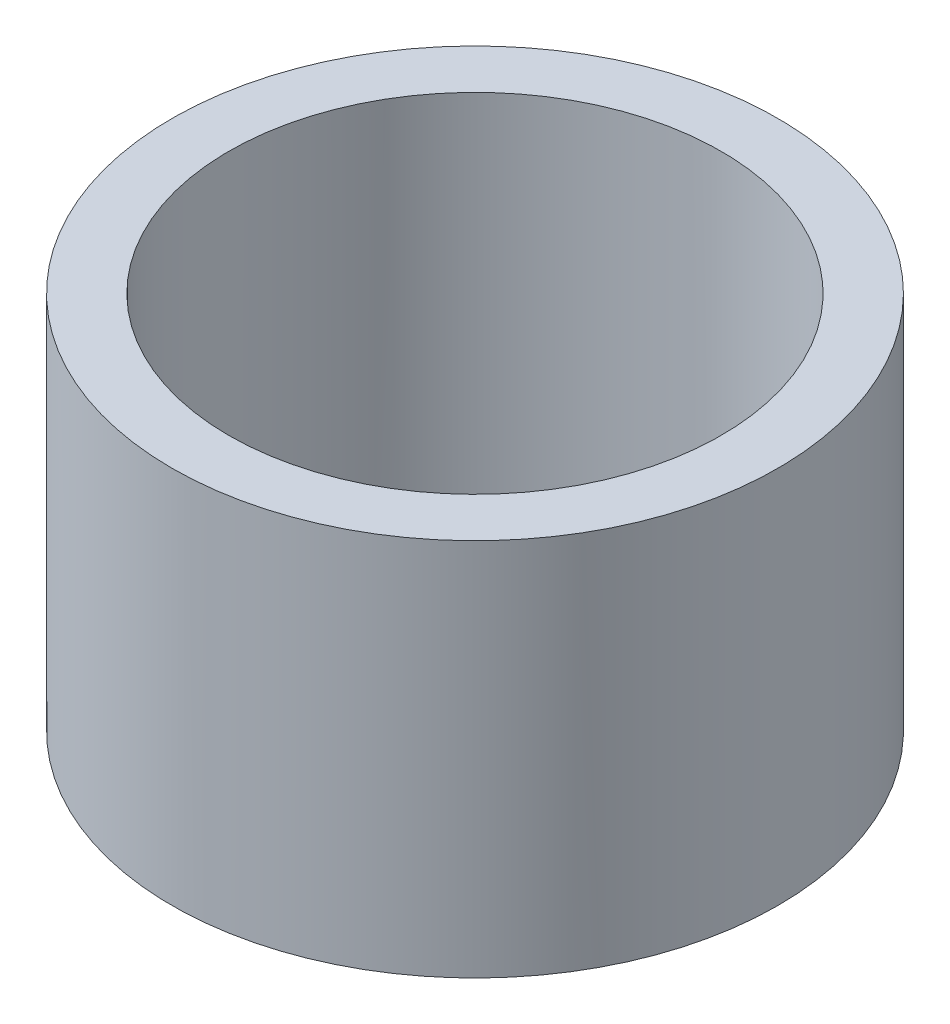
SolidWorks part; units mm, degrees
ref_plane "Front Plane" through (0, 0, 0) normal (0, 0, 1) x (1, 0, 0)
ref_plane "Top Plane" through (0, 0, 0) normal (0, 1, 0) x (1, 0, 0)
ref_plane "Right Plane" through (0, 0, 0) normal (1, 0, 0) x (0, 0, -1)
sketch "Sketch1" plane through (0, 0, 0) normal (0, 1, 0) x (1, 0, 0)
  circle A0 centre (0, 0) radius 20.32
extrude "Boss-Extrude1" add sketch "Sketch1" along normal blind 25.4
sketch "Sketch2" plane through (0, 25.4, 0) normal (0, 1, 0) x (1, 0, 0)
  circle A0 centre (0, 0) radius 16.51
extrude "Cut-Extrude1" cut sketch "Sketch2" against normal through all
sketch "Sketch3" plane through (0, 0, 0) normal (0, 0, 1) x (1, 0, 0)
  circle A0 centre (0, 0) radius 6.35
extrude "Cut-Extrude2" cut sketch "Sketch3" against normal through all
